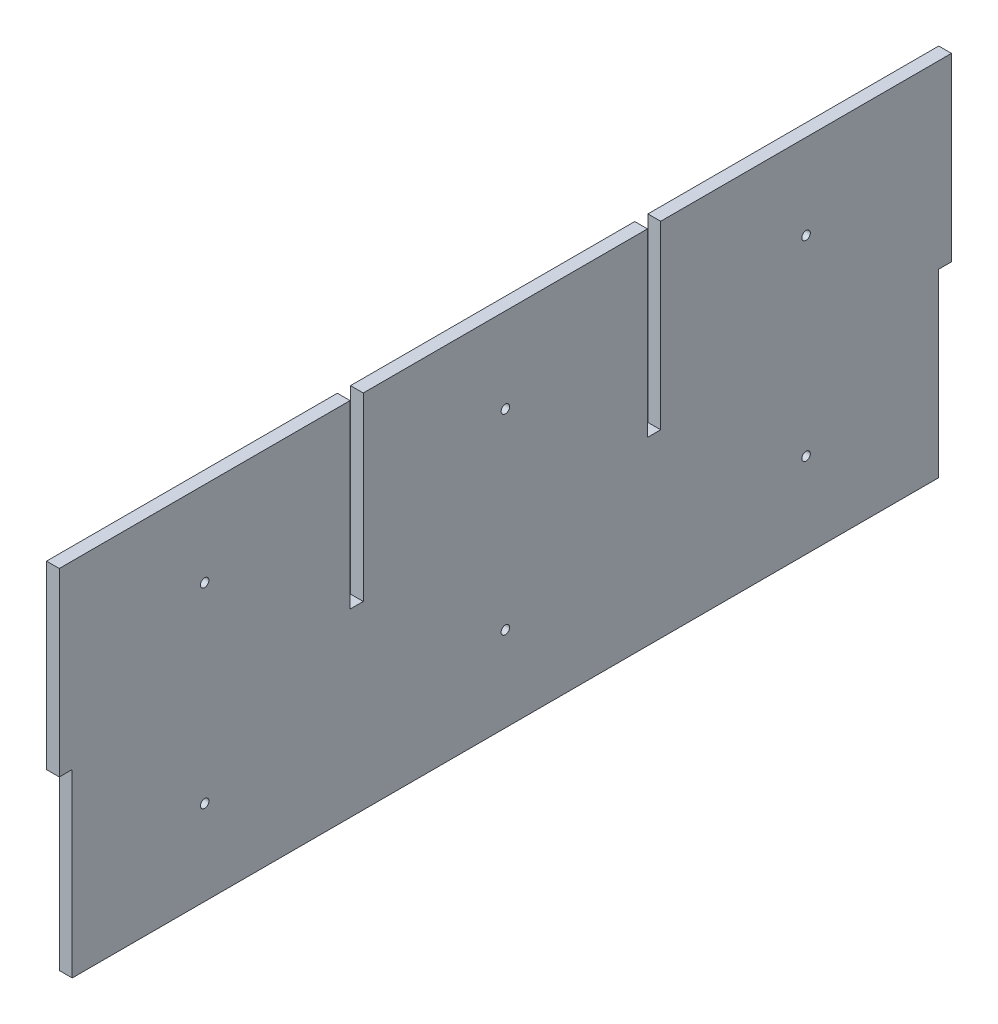
SolidWorks part; units mm, degrees
ref_plane "Front Plane" through (0, 0, 0) normal (0, 0, 1) x (1, 0, 0)
ref_plane "Top Plane" through (0, 0, 0) normal (0, 1, 0) x (1, 0, 0)
ref_plane "Right Plane" through (0, 0, 0) normal (1, 0, 0) x (0, 0, -1)
sketch "Sketch3" plane through (0, 0, 0) normal (1, 0, 0) x (0, 0, -1)
  line L1 (230.9117, 76.9159) -> (650.9117, 76.9159)
  line L2 (230.9117, 76.9159) -> (230.9117, 246.9159)
  line L3 (230.9117, 246.9159) -> (650.9117, 246.9159)
  line L4 (650.9117, 76.9159) -> (650.9117, 246.9159)
  dimension "D1" = 170
  dimension "D2" = 420
extrude "Boss-Extrude2" add sketch "Sketch3" along normal blind 6
sketch "Sketch4" plane through (6, 0, 0) normal (1, 0, 0) x (0, 0, -1)
  line L0 (230.9117, 246.9159) -> (230.9117, 76.9159) construction
  line L1 (230.9117, 161.9159) -> (237.0117, 161.9159)
  line L2 (230.9117, 161.9159) -> (230.9117, 76.9159)
  line L3 (230.9117, 76.9159) -> (237.0117, 76.9159)
  line L4 (237.0117, 161.9159) -> (237.0117, 76.9159)
  line L5 (230.9117, 76.9159) -> (650.9117, 76.9159) construction
  line L6 (650.9117, 76.9159) -> (650.9117, 246.9159) construction
  line L7 (650.9117, 161.9159) -> (644.8117, 161.9159)
  line L8 (650.9117, 161.9159) -> (650.9117, 76.9159)
  line L9 (650.9117, 76.9159) -> (644.8117, 76.9159)
  line L10 (644.8117, 161.9159) -> (644.8117, 76.9159)
  line L11 (650.9117, 246.9159) -> (230.9117, 246.9159) construction
  line L12 (367.8117, 246.9159) -> (374.0117, 246.9159)
  line L13 (367.8117, 246.9159) -> (367.8117, 161.9159)
  line L14 (367.8117, 161.9159) -> (374.0117, 161.9159)
  line L15 (374.0117, 246.9159) -> (374.0117, 161.9159)
  line L17 (514.0117, 246.9159) -> (507.8117, 246.9159)
  line L18 (514.0117, 246.9159) -> (514.0117, 161.9159)
  line L19 (514.0117, 161.9159) -> (507.8117, 161.9159)
  line L20 (507.8117, 246.9159) -> (507.8117, 161.9159)
  point P24 (370.9117, 246.9159)
  point P25 (510.9117, 246.9159)
  dimension "D1" = 6.1
  dimension "D2" = 6.1
  dimension "D3" = 140
  dimension "D4" = 140
  dimension "D5" = 6.2
  dimension "D6" = 6.2
extrude "Cut-Extrude1" cut sketch "Sketch4" against normal blind 6
sketch "Sketch5" plane through (6, 0, 0) normal (1, 0, 0) x (0, 0, -1)
  line L0 (367.8117, 246.9159) -> (230.9117, 246.9159) construction
  line L1 (237.0117, 76.9159) -> (644.8117, 76.9159) construction
  line L2 (507.8117, 246.9159) -> (374.0117, 246.9159) construction
  line L3 (650.9117, 246.9159) -> (514.0117, 246.9159) construction
  circle A0 centre (299.3617, 206.9159) radius 2
  circle A1 centre (299.3617, 116.9159) radius 2
  circle A2 centre (440.9117, 206.9159) radius 2
  circle A3 centre (582.4617, 206.9159) radius 2
  circle A4 centre (582.4617, 116.9159) radius 2
  circle A5 centre (440.9117, 116.9159) radius 2
  dimension "D7" = 4
  dimension "D8" = 4
  dimension "D9" = 4
  dimension "D10" = 4
  dimension "D11" = 4
  dimension "D12" = 4
  dimension "D1" = 40
  dimension "D2" = 40
  dimension "D3" = 40
  dimension "D4" = 40
  dimension "D5" = 40
  dimension "D6" = 40
extrude "Cut-Extrude2" cut sketch "Sketch5" against normal blind 6
